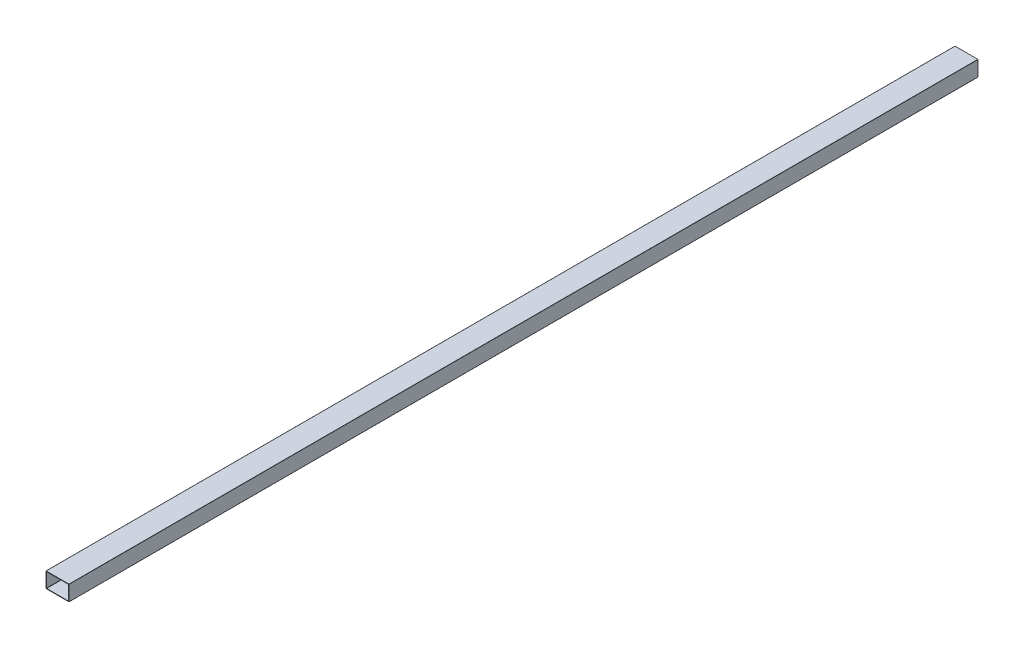
SolidWorks part; units mm, degrees
material "AISI 1035 Acero (SS)"
ref_plane "Alzado" through (0, 0, 0) normal (0, 0, 1) x (1, 0, 0)
ref_plane "Planta" through (0, 0, 0) normal (0, 1, 0) x (1, 0, 0)
ref_plane "Vista lateral" through (0, 0, 0) normal (1, 0, 0) x (0, 0, -1)
sketch "Croquis1" plane through (0, 0, 0) normal (0, 0, 1) x (1, 0, 0)
  line L0 (-73.16, -47.76) -> (-73.16, 47.76)
  line L1 (-76.2, -50.8) -> (76.2, -50.8)
  line L2 (-76.2, -50.8) -> (-76.2, 50.8)
  line L3 (-76.2, 50.8) -> (76.2, 50.8)
  line L4 (76.2, -50.8) -> (76.2, 50.8)
  line L5 (-76.2, -50.8) -> (76.2, 50.8) construction
  line L6 (-76.2, 50.8) -> (76.2, -50.8) construction
  line L7 (-73.16, 47.76) -> (73.16, 47.76)
  line L8 (73.16, -47.76) -> (73.16, 47.76)
  line L9 (-73.16, -47.76) -> (73.16, -47.76)
  point P0 (0, 0)
  dimension "D1" = 101.6
  dimension "D2" = 152.4
  dimension "D3" = 3.04
extrude "Saliente-Extruir1" add sketch "Croquis1" against normal blind 6000
fillet "Redondeo1" radius 1 8 edges at (-73.16, 47.76, -3000) (73.16, 47.76, -3000) (73.16, -47.76, -3000) (-76.2, -50.8, -3000) (-76.2, 50.8, -3000) (-73.16, -47.76, -3000) (76.2, -50.8, -3000) (76.2, 50.8, -3000)
